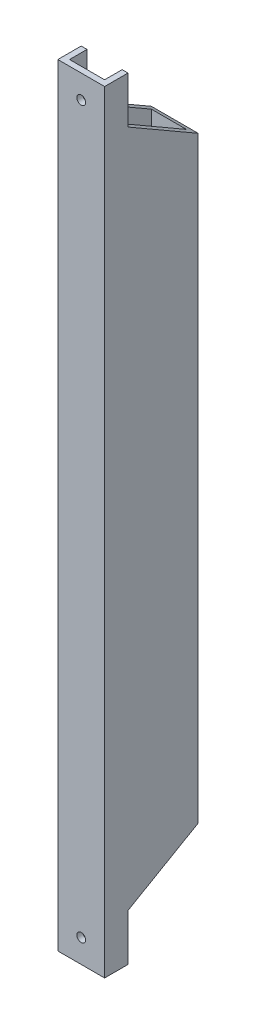
SolidWorks part; units mm, degrees
ref_plane "Front Plane" through (0, 0, 0) normal (0, 0, 1) x (1, 0, 0)
ref_plane "Top Plane" through (0, 0, 0) normal (0, 1, 0) x (1, 0, 0)
ref_plane "Right Plane" through (0, 0, 0) normal (1, 0, 0) x (0, 0, -1)
sketch "Sketch1" plane through (0, 0, 0) normal (0, 1, 0) x (1, 0, 0)
  line L0 (22.225, 3.175) -> (22.225, 47.625)
  line L1 (0, 0) -> (25.4, 0)
  line L2 (0, 0) -> (0, 50.8)
  line L3 (0, 50.8) -> (25.4, 50.8)
  line L4 (25.4, 0) -> (25.4, 50.8)
  line L5 (3.175, 47.625) -> (22.225, 47.625)
  line L6 (3.175, 3.175) -> (3.175, 47.625)
  line L7 (3.175, 3.175) -> (22.225, 3.175)
  dimension "D2" = 25.4
  dimension "D3" = 50.8
  dimension "D1" = 3.175
extrude "Boss-Extrude1" add sketch "Sketch1" along normal blind 419.1
hole_wizard "#10 Clearance Hole1" positions "Sketch3" profile "Sketch4" hole size "#10" standard "ANSI Inch" end condition through all
sketch "Sketch3" plane through (0, 0, -50.8) normal (0, 0, -1) x (-1, 0, 0)
  line L0 (-25.4, 419.1) -> (0, 419.1) construction
  line L1 (0, 419.1) -> (0, 0) construction
  line L2 (13.97, 0) -> (-13.97, 0) construction
  point P0 (-12.7, 406.4)
  point P2 (-12.7, 12.7)
  dimension "D1" = 12.7
  dimension "D2" = 12.7
  dimension "D3" = 12.7
  dimension "D4" = 12.7
sketch "Sketch4" plane through (12.7, 406.4, -50.8) normal (1, 0, 0) x (0, 1, 0)
  line L0 (0, 0) -> (0, 50.8)
  line L1 (0, 50.8) -> (2.3812, 50.8)
  line L2 (2.3812, 50.8) -> (2.3812, 0)
  line L5 (2.3812, 0) -> (0, 0)
  line L11 (0, -6.35) -> (0, 107.95) construction
  dimension "Thru Hole Dia." = 4.7625
  dimension "Thru Hole Depth" = 50.8
sketch "Sketch5" plane through (25.4, 0, 0) normal (1, 0, 0) x (0, 0, -1)
  line L0 (12.7, 419.1) -> (12.7, 393.7)
  line L1 (0, 419.1) -> (50.8, 419.1) construction
  line L2 (12.7, 393.7) -> (50.8, 371.703)
  line L3 (50.8, 419.1) -> (50.8, 0) construction
  line L4 (50.8, 371.703) -> (50.8, 419.1)
  line L5 (50.8, 419.1) -> (12.7, 419.1)
  line L6 (0, 419.1) -> (0, 0) construction
  dimension "D1" = 25.4
  dimension "D2" = 120
  dimension "D3" = 12.7
extrude "Cut-Extrude1" cut sketch "Sketch5" against normal through all
ref_plane "Plane1" through (0, 209.55, 0) normal (0, 1, 0) x (1, 0, 0)
mirror "Mirror1" about plane through (0, 209.55, 0) normal (0, 1, 0) of "Cut-Extrude1"
sketch "Sketch6" plane through (0, 0, -50.8) normal (0, 0, -1) x (-1, 0, 0)
  line L0 (45.7131, 209.55) -> (-45.7131, 209.55) construction
  line L1 (0, 371.703) -> (0, 47.397) construction
  circle A0 centre (-12.7, 121.2725) radius 2.1828
  circle A1 centre (-12.7, 297.8275) radius 2.1828
  point P8 (0, 0)
  dimension "D1" = 4.3656
  dimension "D2" = 4.3656
  dimension "D3" = 88.2775
  dimension "D4" = 88.2775
  dimension "D5" = 12.7
extrude "Cut-Extrude2" cut sketch "Sketch6" against normal up to next
